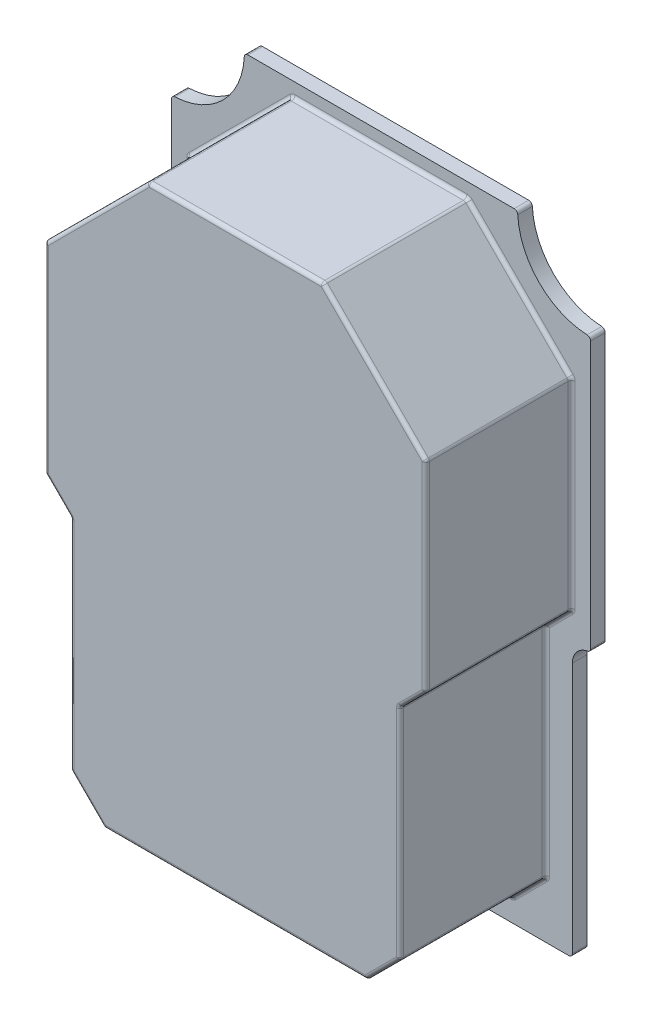
SolidWorks part; units mm, degrees
ref_plane "Ön Düzlem" through (0, 0, 0) normal (0, 0, 1) x (1, 0, 0)
ref_plane "Üst Düzlem" through (0, 0, 0) normal (0, 1, 0) x (1, 0, 0)
ref_plane "Sağ Düzlem" through (0, 0, 0) normal (1, 0, 0) x (0, 0, -1)
sketch "Çizim1" plane through (0, 0, 0) normal (0, 0, 1) x (1, 0, 0)
  line L1 (20, 0) -> (95, 0)
  line L2 (0, -20) -> (0, -95)
  line L3 (5, -170) -> (110, -170)
  line L4 (115, -20) -> (115, -95)
  line L5 (110, -100) -> (110, -170)
  line L6 (5, -100) -> (5, -170)
  arc A0 (95, 0) -> (115, -20) centre (115, 0) ccw
  arc A1 (0, -20) -> (20, 0) centre (0, 0) ccw
  arc A2 (5, -100) -> (0, -95) centre (0, -100) ccw
  arc A3 (115, -95) -> (110, -100) centre (115, -100) ccw
  dimension "D3" = 40
  dimension "D4" = 40
  dimension "D6" = 10
  dimension "D7" = 10
  dimension "D1" = 115
extrude "Yükseklik-Ekstrüzyon5" add sketch "Çizim1" along normal blind 4
sketch "Çizim6" plane through (0, 0, 4) normal (0, 0, 1) x (1, 0, 0)
  line L1 (95, 0) -> (20, 0) construction
  line L2 (33.5, -4) -> (81.5, -4)
  line L3 (81.5, -4) -> (109.7843, -32.2843)
  line L4 (109.7843, -32.2843) -> (109.7843, -87.2843)
  line L5 (109.7843, -87.2843) -> (102.7132, -94.3553)
  line L6 (102.7132, -94.3553) -> (102.7132, -154.3553)
  line L7 (102.7132, -154.3553) -> (93.5208, -163.5477)
  line L8 (93.5208, -163.5477) -> (21.4792, -163.5477)
  line L9 (12.2868, -154.3553) -> (21.4792, -163.5477)
  line L10 (12.2868, -94.3553) -> (12.2868, -154.3553)
  line L11 (5.2157, -87.2843) -> (12.2868, -94.3553)
  line L12 (5.2157, -32.2843) -> (5.2157, -87.2843)
  line L13 (33.5, -4) -> (5.2157, -32.2843)
  point P13 (57.5, -163.5477)
  point P18 (57.5, -4)
  dimension "D1" = 24
  dimension "D2" = 40
  dimension "D3" = 4
  dimension "D4" = 55
  dimension "D5" = 10
  dimension "D6" = 60
  dimension "D7" = 13
extrude "Yükseklik-Ekstrüzyon6" add sketch "Çizim6" along normal blind 40
fillet "Radyus2" radius 1 44 edges at (109.7843, -59.7843, 44) (109.7843, -59.7843, 4) (115, -95, 2) (106.2487, -90.8198, 4) (109.7843, -87.2843, 24) (106.2487, -90.8198, 44) (102.7132, -94.3553, 24) (102.7132, -124.3553, 4) (102.7132, -124.3553, 44) (110, -170, 2) (98.117, -158.9515, 4) (102.7132, -154.3553, 24) (98.117, -158.9515, 44) (93.5208, -163.5477, 24) (5, -170, 2) (57.5, -163.5477, 44) (57.5, -163.5477, 4) (0, -95, 2) (8.7513, -90.8198, 44) (8.7513, -90.8198, 4) (12.2868, -94.3553, 24) (5.2157, -87.2843, 24) (12.2868, -124.3553, 4) (12.2868, -124.3553, 44) (16.883, -158.9515, 44) (16.883, -158.9515, 4) (21.4792, -163.5477, 24) (12.2868, -154.3553, 24) (57.5, -4, 4) (33.5, -4, 24) (5.2157, -59.7843, 4) (5.2157, -59.7843, 44) (5.2157, -32.2843, 24) (19.3579, -18.1421, 4) (19.3579, -18.1421, 44) (0, -20, 2) (20, 0, 2) (57.5, -4, 44) (95.6421, -18.1421, 44) (81.5, -4, 24) (95.6421, -18.1421, 4) (109.7843, -32.2843, 24) (115, -20, 2) (95, 0, 2)
sketch "Çizim8" plane through (0, 0, 0) normal (0, 0, -1) x (-1, 0, 0)
  line L1 (-94.0238, 0) -> (-20.9762, 0) construction
  line L2 (-81.5, -5) -> (-33.5, -5)
  line L3 (-33.5, -5) -> (-5.2157, -33.2843)
  line L4 (-5.2157, -33.2843) -> (-5.2157, -88.2843)
  line L5 (-5.2157, -88.2843) -> (-12.2868, -95.3553)
  line L7 (-12.2868, -95.3553) -> (-12.2868, -153.3553)
  line L9 (-12.2868, -153.3553) -> (-21.4792, -162.5477)
  line L10 (-21.4792, -162.5477) -> (-93.5208, -162.5477)
  line L11 (-102.7132, -153.3553) -> (-93.5208, -162.5477)
  line L12 (-102.7132, -95.3553) -> (-102.7132, -153.3553)
  line L13 (-109.7843, -88.2843) -> (-102.7132, -95.3553)
  line L14 (-109.7843, -33.2843) -> (-109.7843, -88.2843)
  line L15 (-81.5, -5) -> (-109.7843, -33.2843)
  point P13 (-57.5, -162.5477)
  point P18 (-57.5, -5)
  dimension "D1" = 5
  dimension "D2" = 24
  dimension "D3" = 40
  dimension "D4" = 55
  dimension "D5" = 10
  dimension "D6" = 58
  dimension "D7" = 13
extrude "Kes-Ekstrüzyon1" cut sketch "Çizim8" against normal blind 4
sketch "Çizim9" plane through (0, 0, 4) normal (0, 0, -1) x (-1, 0, 0)
  line L2 (-80.5, -7) -> (-34.5, -7)
  line L3 (-33.5, -5) -> (-81.5, -5) construction
  line L4 (-34.5, -7) -> (-6.9228, -34.5772)
  line L6 (-6.9228, -34.5772) -> (-6.9228, -86.5772)
  line L13 (-6.9228, -86.5772) -> (-14.701, -94.3553)
  line L15 (-14.701, -94.3553) -> (-14.701, -150.3553)
  line L19 (-14.701, -150.3553) -> (-22.4792, -158.1335)
  line L20 (-22.4792, -158.1335) -> (-92.5208, -158.1335)
  line L22 (-100.299, -150.3553) -> (-92.5208, -158.1335)
  line L23 (-100.299, -94.3553) -> (-100.299, -150.3553)
  line L24 (-108.0772, -86.5772) -> (-100.299, -94.3553)
  line L25 (-108.0772, -34.5772) -> (-108.0772, -86.5772)
  line L26 (-80.5, -7) -> (-108.0772, -34.5772)
  point P14 (-57.5, -158.1335)
  point P20 (-57.5, -7)
  dimension "D1" = 2
  dimension "D2" = 39
  dimension "D3" = 52
  dimension "D4" = 23
  dimension "D5" = 11
  dimension "D6" = 56
  dimension "D7" = 11
extrude "Kes-Ekstrüzyon2" cut sketch "Çizim9" against normal blind 35
